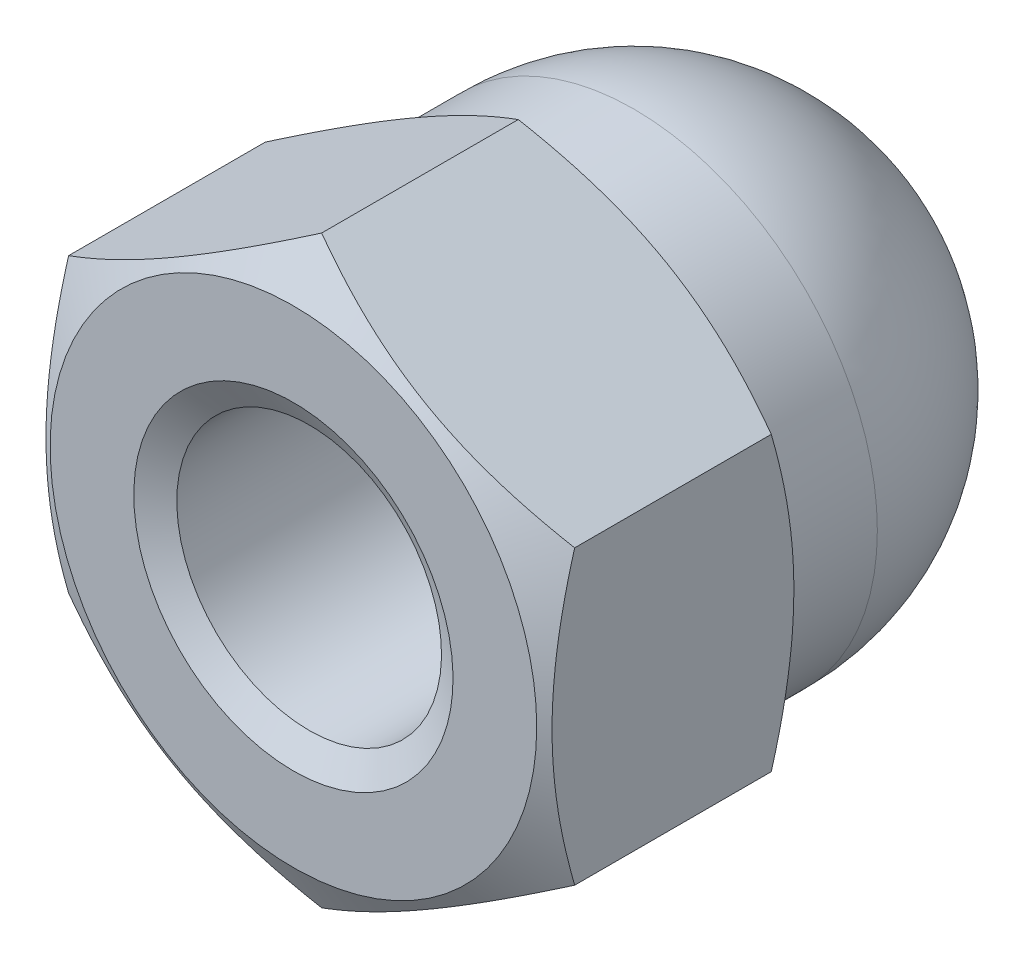
SolidWorks part; units mm, degrees
ref_plane "Front Plane" through (0, 0, 0) normal (0, 0, 1) x (1, 0, 0)
ref_plane "Top Plane" through (0, 0, 0) normal (0, 1, 0) x (1, 0, 0)
ref_plane "Right Plane" through (0, 0, 0) normal (1, 0, 0) x (0, 0, -1)
sketch "Sketch1" plane through (0, 0, 0) normal (0, 0, 1) x (1, 0, 0)
  line L0 (0, 0) -> (6.5, 0) construction
  line L8 (0, 7.5056) -> (-6.5, 3.7528)
  line L9 (-6.5, 3.7528) -> (-6.5, -3.7528)
  line L10 (-6.5, -3.7528) -> (0, -7.5056)
  line L11 (0, -7.5056) -> (6.5, -3.7528)
  line L12 (6.5, -3.7528) -> (6.5, 3.7528)
  line L13 (6.5, 3.7528) -> (0, 7.5056)
  circle A0 centre (0, 0) radius 6.5 construction
  dimension "E" = 13
extrude "Boss-Extrude1" add sketch "Sketch1" against normal blind 15
sketch "Sketch2" plane through (0, 0, 0) normal (1, 0, 0) x (0, 0, -1)
  line L0 (0, 0) -> (29.4916, 0) construction
  line L2 (16, 0) -> (15, 0)
  line L4 (0, 7.5056) -> (0, 3.7528) construction
  line L5 (16, 30.5536) -> (6.5, 30.5536)
  line L6 (6.5, 30.5536) -> (6.5, 6.25)
  line L7 (16, 0) -> (16, 30.5536)
  line L8 (6.5, 6.25) -> (8.75, 6.25)
  arc A2 (8.75, 6.25) -> (15, 0) centre (8.75, 0) cw
  dimension "D2" = 1
  dimension "SR(r)" = 6.25
  dimension "HIGHERTHNh" = 16
  dimension "HVALUE" = 15
  dimension "dk" = 12.5
  dimension "CIRC" = 12.5
  dimension "M" = 6.5
revolve "Cut-Revolve7" cut sketch "Sketch2" angle 360 about L0
sketch "Sketch3" plane through (0, 0, 0) normal (1, 0, 0) x (0, 0, -1)
  line L0 (5.7751, 7.5056) -> (6.5, 7.5056)
  line L1 (6.5, 7.5056) -> (6.5, 3.7528) construction
  line L2 (6.5, 7.5056) -> (6.5, 6.25)
  line L3 (0, 6.25) -> (0, 7.5056)
  line L4 (6.5, 6.25) -> (5.7751, 7.5056)
  line L5 (0, 0) -> (7.2855, 0) construction
  line L9 (0, 7.5056) -> (0, 3.7528) construction
  line L10 (0, 7.5056) -> (0.7249, 7.5056)
  line L11 (0.7249, 7.5056) -> (0, 6.25)
  line L12 (6.5, 7.5056) -> (0, 7.5056) construction
  line L13 (8.75, 6.25) -> (6.5, 6.25) construction
  line L14 (6.5, 7.5056) -> (0, 7.5056) construction
  dimension "D2" = 30
  dimension "D4" = 30
revolve "Cut-Revolve8" cut sketch "Sketch3" angle 360 about L5
sketch "Sketch4" plane through (0, 0, 0) normal (1, 0, 0) x (0, 0, -1)
  line L0 (0, 0) -> (15, 0) construction
  line L1 (0, 4.1) -> (0.4041, 3.4)
  line L2 (0, 6.25) -> (0, -6.25) construction
  line L3 (0.4041, 3.4) -> (10.65, 3.4)
  line L7 (10.65, 3.4) -> (13, 0)
  line L8 (13, 0) -> (0, 0)
  line L9 (0, 0) -> (0, 4.1)
  dimension "D1" = 2
  dimension "D2" = 6.8
  dimension "D3" = 10.65
  dimension "D4" = 8.2
  dimension "D5" = 60
revolve "Cut-Revolve9" cut sketch "Sketch4" angle 360 about L0
cosmetic thread "Cosmetic Thread1" parameters "D1"=8.15, "D2"=8
sketch "Sketch5" plane through (0, 0, 0) normal (1, 0, 0) x (0, 0, -1)
  line L0 (0, 0) -> (15, 0) construction
  line L1 (0, 4.1) -> (0.4041, 3.4)
  line L8 (12, 0) -> (0, 0)
  line L9 (0, 0) -> (0, 4.1)
  line L10 (0.4041, 3.4) -> (8.76, 3.4)
  line L11 (8.76, 3.4) -> (9.46, 4.1)
  line L12 (9.46, 4.1) -> (15.16, 4.1)
  line L13 (15.16, 4.1) -> (15.16, 3.4)
  line L14 (15.16, 3.4) -> (12, 0)
  dimension "D1" = 3
  dimension "D2" = 6.8
  dimension "D3" = 45
  dimension "D4" = 8.2
  dimension "D5" = 60
  dimension "D6" = 6.4
  dimension "D7" = 15.16
